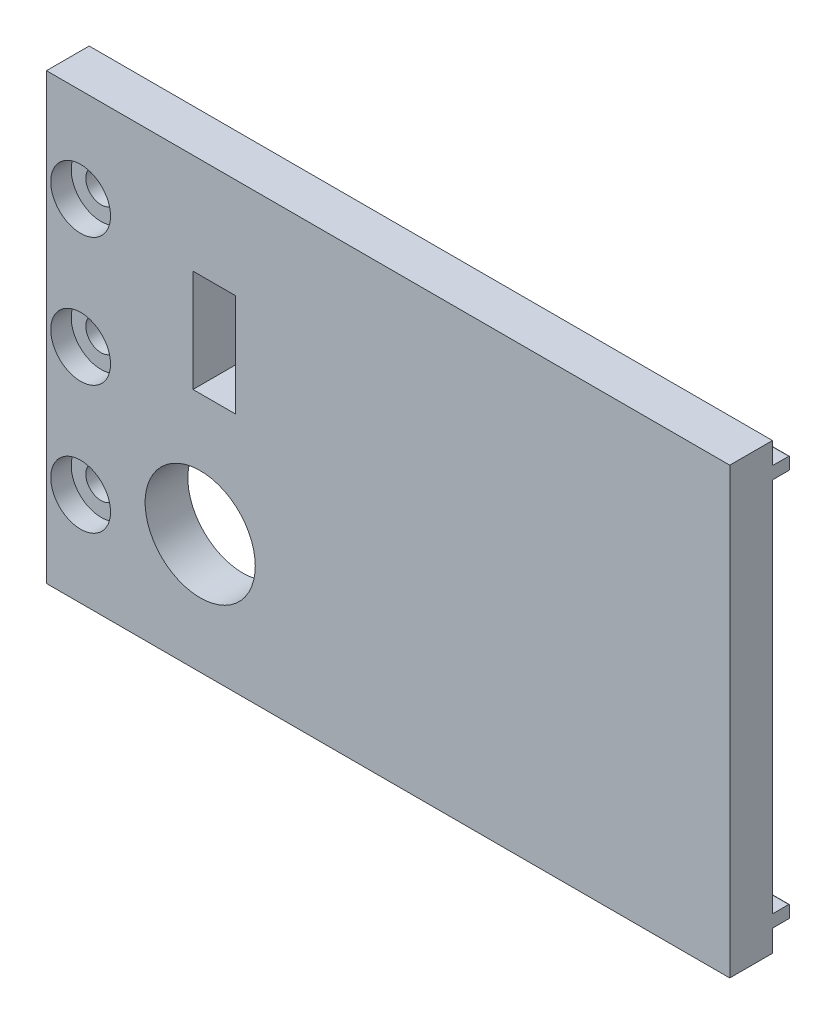
SolidWorks part; units mm, degrees
material "ABS"
ref_plane "Plan de face" through (0, 0, 0) normal (0, 0, 1) x (1, 0, 0)
ref_plane "Plan de dessus" through (0, 0, 0) normal (0, 1, 0) x (1, 0, 0)
ref_plane "Plan de droite" through (0, 0, 0) normal (1, 0, 0) x (0, 0, -1)
sketch "Esquisse1" plane through (0, 0, 16.9801) normal (0, 0, 1) x (1, 0, 0)
  line L1 (-84.4443, 50.0666) -> (-4.4443, 50.0666)
  line L2 (-84.4443, 50.0666) -> (-84.4443, -1.9334)
  line L3 (-84.4443, -1.9334) -> (-4.4443, -1.9334)
  line L4 (-4.4443, 50.0666) -> (-4.4443, -1.9334)
extrude "Boss.-Extru.1" add sketch "Esquisse1" along normal blind 5
sketch "Esquisse2" plane through (0, 0, 21.9801) normal (0, 0, 1) x (1, 0, 0)
  line L0 (-84.4443, 50.0666) -> (-84.4443, -1.9334) construction
  line L1 (-84.4443, -1.9334) -> (-4.4443, -1.9334) construction
  circle A0 centre (-66.4443, 12.0617) radius 6.4479
  dimension "D1" = 12.8957
  dimension "D2" = 18
  dimension "D3" = 13.9952
extrude "Enlèv. mat.-Extru.1" cut sketch "Esquisse2" against normal blind 5
hole_wizard "Chambrage pour vis à tête ronde bombée M34" positions "Esquisse3" profile "Esquisse4" counterbore size "M3" standard "Ansi Metric" end condition up to next
sketch "Esquisse3" plane through (0, 0, 21.9801) normal (0, 0, 1) x (1, 0, 0)
  line L0 (-84.4443, -1.9334) -> (-4.4443, -1.9334) construction
  line L1 (-84.4443, 50.0666) -> (-84.4443, -1.9334) construction
  point P0 (-80.4443, 9.0666)
  point P2 (-80.4443, 24.0666)
  point P4 (-80.4443, 39.0666)
  dimension "D1" = 11
  dimension "D2" = 4
  dimension "D3" = 4
  dimension "D4" = 4
  dimension "D5" = 15
  dimension "D6" = 15
sketch "Esquisse4" plane through (-80.4443, 9.0666, 21.9801) normal (1, 0, 0) x (0, -1, 0)
  line L0 (0, 0) -> (0, 5)
  line L1 (0, 5) -> (1.8, 5)
  line L3 (1.8, 5) -> (1.8, 2.4)
  line L4 (1.8, 2.4) -> (3.5, 2.4)
  line L5 (3.5, 2.4) -> (3.5, 0)
  line L7 (3.5, 0) -> (0, 0)
  line L11 (0, -6.35) -> (0, 107.95) construction
  dimension "Diamètre du perçage jusqu'au prochain" = 3.6
  dimension "Profondeur du perçage jusqu'au prochain" = 5
  dimension "Diamètre du chambrage" = 7
  dimension "Profondeur du chambrage" = 2.4
sketch "Esquisse5" plane through (0, 0, 16.9801) normal (0, 0, -1) x (-1, 0, 0)
  line L0 (4.4443, -1.9334) -> (4.4443, 50.0666) construction
  line L1 (4.4443, 2.0666) -> (76.4443, 2.0666)
  line L2 (4.4443, 2.0666) -> (4.4443, 0.6166)
  line L3 (4.4443, 0.6166) -> (76.4443, 0.6166)
  line L4 (76.4443, 2.0666) -> (76.4443, 0.6166)
  line L5 (84.4443, -1.9334) -> (4.4443, -1.9334) construction
  line L6 (86.3891, 24.0666) -> (2.4995, 24.0666) construction
  line L7 (76.4443, 46.0666) -> (76.4443, 47.5166)
  line L8 (4.4443, 46.0666) -> (4.4443, 47.5166)
  line L9 (4.4443, 47.5166) -> (76.4443, 47.5166)
  line L10 (4.4443, 46.0666) -> (76.4443, 46.0666)
  dimension "D1" = 0
  dimension "D2" = 4
  dimension "D3" = 1.45
  dimension "D4" = 72
extrude "Boss.-Extru.2" add sketch "Esquisse5" along normal blind 2
fillet "Congé1" radius 0.1 8 edges at (-40.4443, 0.6166, 14.9801) (-40.4443, 2.0666, 14.9801) (-40.4443, 47.5166, 14.9801) (-40.4443, 46.0666, 14.9801) (-40.4443, 46.0666, 16.9801) (-40.4443, 47.5166, 16.9801) (-40.4443, 2.0666, 16.9801) (-40.4443, 0.6166, 16.9801)
sketch "Esquisse6" plane through (0, 0, 21.9801) normal (0, 0, 1) x (1, 0, 0)
  line L1 (-67.2885, 38.3184) -> (-62.2885, 38.3184)
  line L2 (-67.2885, 38.3184) -> (-67.2885, 26.3184)
  line L3 (-67.2885, 26.3184) -> (-62.2885, 26.3184)
  line L4 (-62.2885, 38.3184) -> (-62.2885, 26.3184)
  dimension "D1" = 12
  dimension "D2" = 5
extrude "Enlèv. mat.-Extru.2" cut sketch "Esquisse6" against normal through all contours L2 L3 L4 L1
